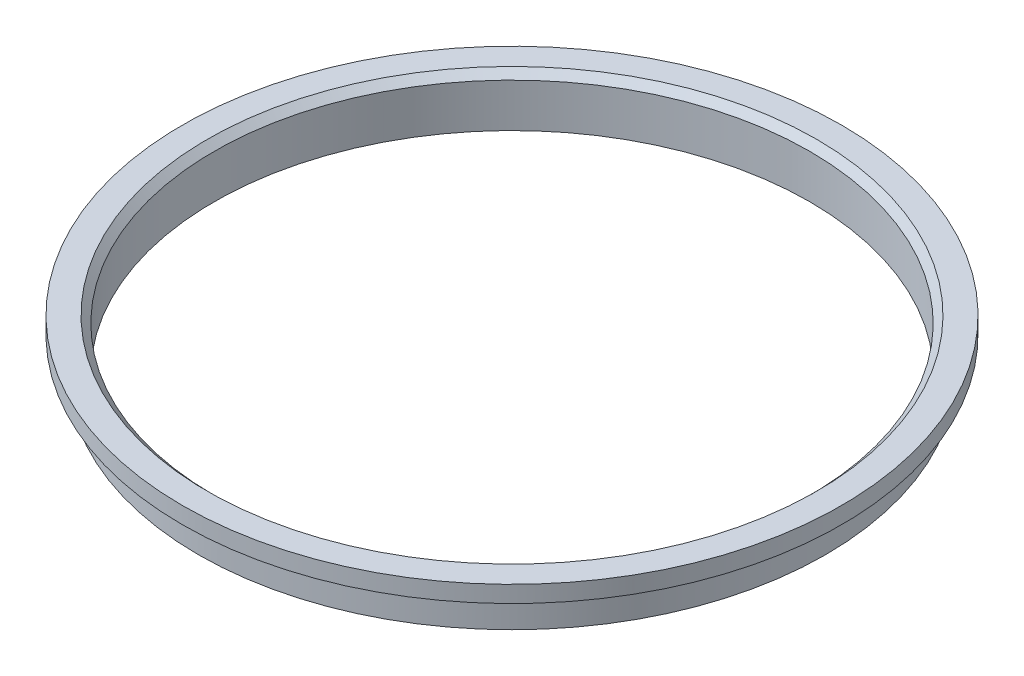
SolidWorks part; units mm, degrees
material "AISI 4340 Steel, annealed"
ref_plane "Front Plane" through (0, 0, 0) normal (0, 0, 1) x (1, 0, 0)
ref_plane "Top Plane" through (0, 0, 0) normal (0, 1, 0) x (1, 0, 0)
ref_plane "Right Plane" through (0, 0, 0) normal (1, 0, 0) x (0, 0, -1)
sketch "Sketch1" plane through (0, 0, 0) normal (0, 0, 1) x (1, 0, 0)
  line L0 (0, 0) -> (0, 24.8476) construction
  line L1 (0, 0) -> (-54.5528, 0) construction
  line L2 (-54.5528, 0) -> (-54.5528, -9.271)
  line L3 (-54.5528, -9.271) -> (-57.4357, -9.271)
  line L4 (-57.4357, -9.271) -> (-57.4357, -3.048)
  line L5 (-57.4357, -3.048) -> (-60.3631, -3.048)
  line L6 (-60.3631, -3.048) -> (-60.3631, 0)
  line L7 (-60.3631, 0) -> (-54.5528, 0)
  dimension "D1" = 60.3631
  dimension "D2" = 9.271
  dimension "D3" = 3.048
  dimension "D4" = 54.5528
  dimension "D5" = 57.4357
revolve "Revolve1" add sketch "Sketch1" angle 360 about L0
chamfer "Chamfer1" distance 1.27 angle 45 1 edges at (0, 0, -54.5528)
fillet "Fillet1" radius 1.5875 1 edges at (0, -3.048, -57.4357)
